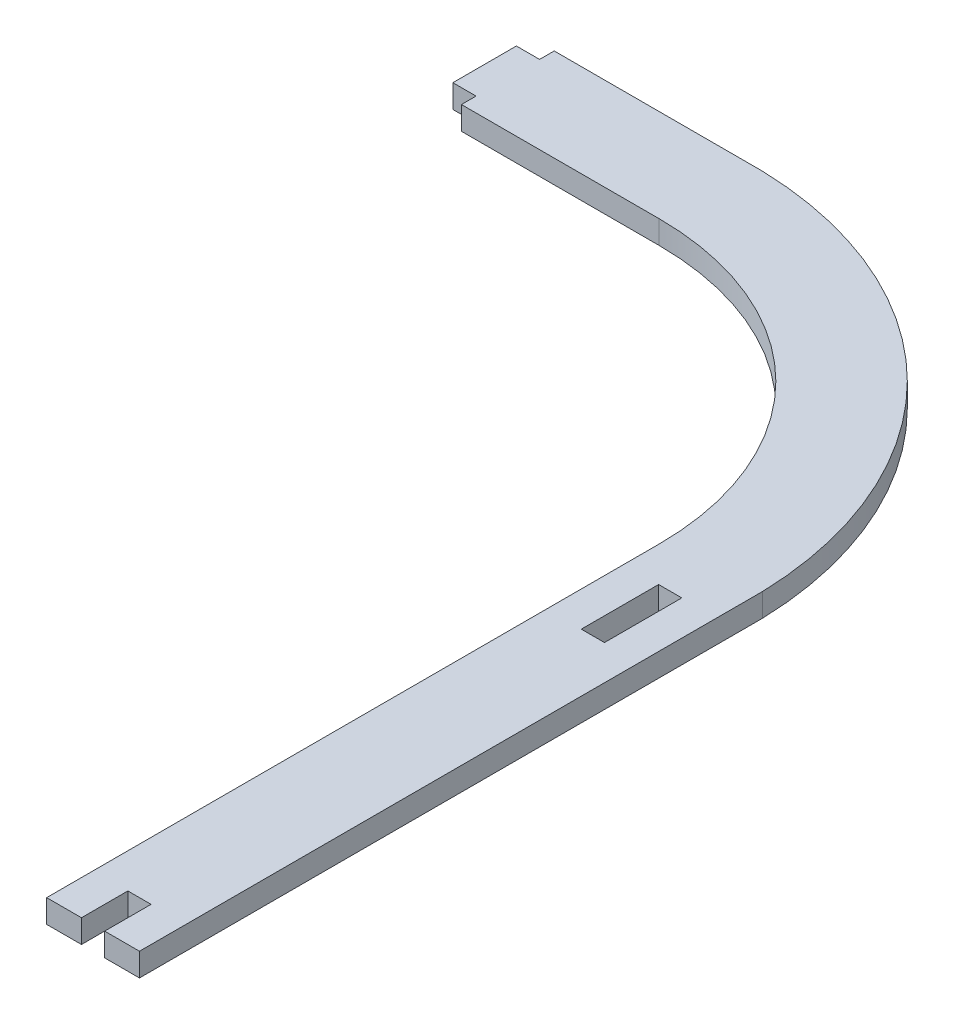
SolidWorks part; units mm, degrees
ref_plane "Alzado" through (0, 0, 0) normal (0, 0, 1) x (1, 0, 0)
ref_plane "Planta" through (0, 0, 0) normal (0, 1, 0) x (1, 0, 0)
ref_plane "Vista lateral" through (0, 0, 0) normal (1, 0, 0) x (0, 0, -1)
sketch "Croquis1" plane through (0, 0, 0) normal (0, 1, 0) x (1, 0, 0)
  line L0 (0, 0) -> (0, 8)
  line L1 (0, 8) -> (3, 8)
  line L2 (3, -2.107) -> (3, -0.2139)
  line L3 (3, 9.893) -> (7.3583, 9.893)
  line L4 (3, 3.893) -> (72.5, 3.893) construction
  line L5 (72.5, 3.893) -> (72.5, -105.737) construction
  line L6 (3, -2.107) -> (7.3583, -2.107)
  line L7 (0, -0.2139) -> (3, -0.2139)
  line L8 (0, 7.7861) -> (0, -0.2139)
  line L9 (3, 8) -> (3, 9.893)
  line L10 (72.5, -111.737) -> (72.5, -117.737)
  line L11 (72.5, -105.737) -> (72.5, -111.737) construction
  line L12 (72.5, -111.737) -> (69.5, -111.737)
  line L13 (69.5, -111.737) -> (69.5, -117.737)
  line L14 (7.3583, -2.107) -> (28.5736, -2.107)
  line L15 (69.5, -117.737) -> (65, -117.737)
  line L16 (72.5, -117.737) -> (77, -117.737)
  line L18 (7.3583, 9.893) -> (29.9532, 9.893)
  line L19 (71, 3.893) -> (28.5736, -38.5334) construction
  line L20 (65, -117.737) -> (65, -38.5334)
  line L21 (71, -105.737) -> (71, 3.893) construction
  line L22 (77, -117.737) -> (77, -37.1537)
  line L24 (71, -34.607) -> (71, -61.607) construction
  line L25 (69.5, -48.107) -> (69.5, -43.107)
  line L26 (69.5, -43.107) -> (72.5, -43.107)
  line L27 (72.5, -43.107) -> (72.5, -53.107)
  line L28 (72.5, -53.107) -> (69.5, -53.107)
  line L29 (69.5, -53.107) -> (69.5, -48.107)
  arc A0 (65, -38.5334) -> (28.5736, -2.107) centre (28.5736, -38.5334) ccw
  arc A2 (77, -37.1537) -> (29.9532, 9.893) centre (28.5736, -38.5334) ccw
  dimension "D1" = 8
  dimension "D2" = 3
  dimension "D3" = 6
  dimension "D4" = 69.5
  dimension "D5" = 109.63
  dimension "D6" = 38.5
  dimension "D7" = 6
  dimension "D8" = 6
  dimension "D9" = 65.5
  dimension "D11" = 5
  dimension "D12" = 60
  dimension "D13" = 10
extrude "Saliente-Extruir1" add sketch "Croquis1" along normal blind 3 contours L22 A2 L18 L3 L9 L1 L0 L8 L7 L2 L6 L14 A0 L20 L15 L13 L12 L10 L16
